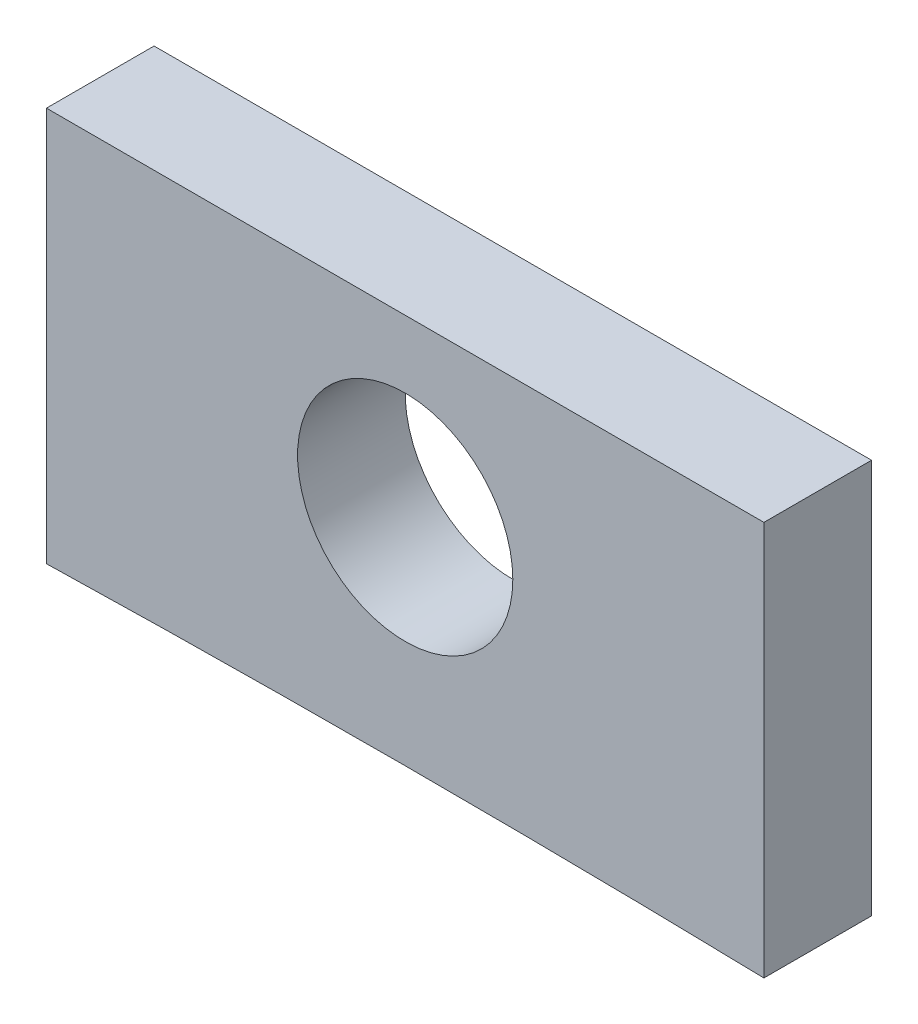
SolidWorks part; units mm, degrees
ref_plane "Спереди" through (0, 0, 0) normal (0, 0, 1) x (1, 0, 0)
ref_plane "Сверху" through (0, 0, 0) normal (0, 1, 0) x (1, 0, 0)
ref_plane "Справа" through (0, 0, 0) normal (1, 0, 0) x (0, 0, -1)
sketch "Эскиз1" plane through (0, 0, 0) normal (0, 0, 1) x (1, 0, 0)
  line L0 (-10, 699.8768) -> (10, 699.8768)
  line L1 (-10, 699.8768) -> (-10, 688.8768)
  line L2 (10, 699.8768) -> (10, 688.8768)
  arc A1 (374.4506, 126.0836) -> (-374.4506, 126.0836) centre (0, 283) ccw construction
  circle A3 centre (0, 695) radius 3
  circle A4 centre (0, 695) radius 3 construction
  arc A5 (-10, 688.8768) -> (10, 688.8768) centre (0, 283) cw
  dimension "D1" = 20
  dimension "D2" = 11
extrude "Бобышка-Вытянуть1" add sketch "Эскиз1" along normal blind 3
